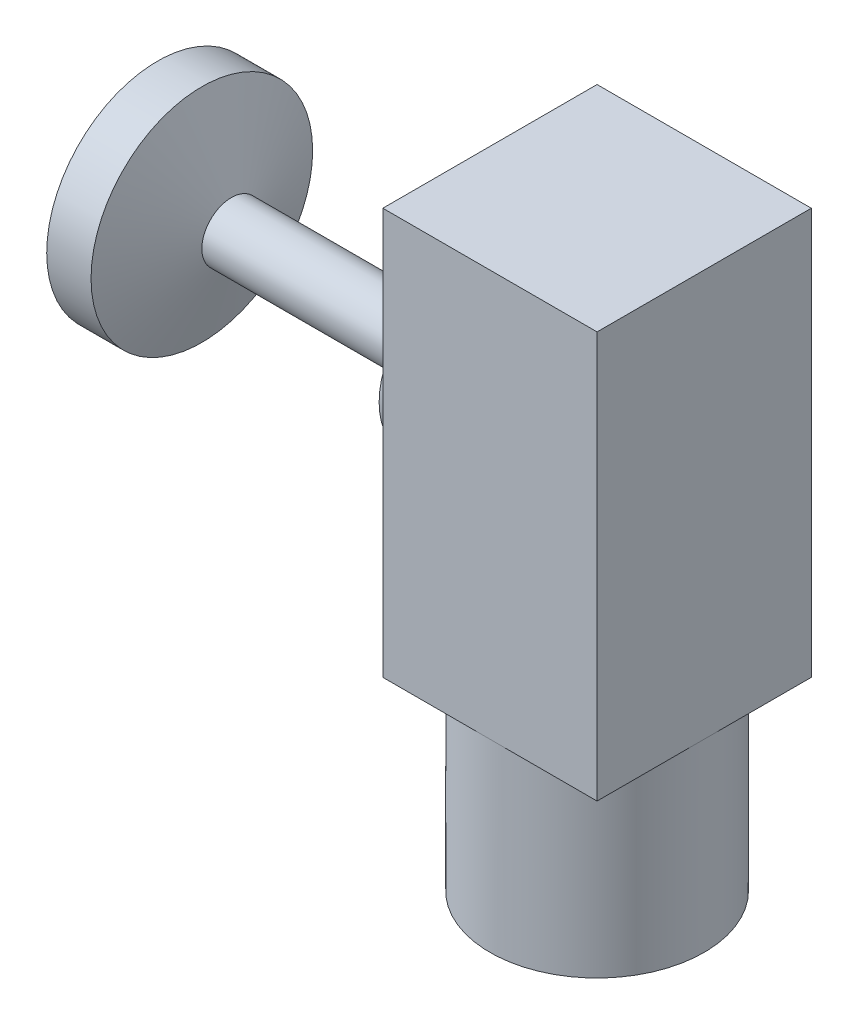
SolidWorks part; units mm, degrees
ref_plane "前视基准面" through (0, 0, 0) normal (0, 0, 1) x (1, 0, 0)
ref_plane "上视基准面" through (0, 0, 0) normal (0, 1, 0) x (1, 0, 0)
ref_plane "右视基准面" through (0, 0, 0) normal (1, 0, 0) x (0, 0, -1)
other "Configuration Table"
sketch "草图1" plane through (0, 0, 0) normal (0, 0, 1) x (1, 0, 0)
  line L0 (-10, 15) -> (-10, 0)
  line L2 (-10, 0) -> (35, 0)
  line L3 (-10, 15) -> (-4, 15)
  line L4 (-4, 15) -> (0, 4)
  line L7 (0, 4) -> (30, 4)
  line L9 (30, 4) -> (30, 10)
  line L10 (30, 10) -> (35, 10)
  line L14 (35, 0) -> (35, 10)
  point P5 (0, 0)
  dimension "D1" = 10
  dimension "D2" = 15
  dimension "D3" = 10
  dimension "D4" = 6
  dimension "D5" = 30
  dimension "D6" = 4
  dimension "D7" = 5
revolve "旋转3" add sketch "草图1" angle 360 about L2
sketch "草图2" plane through (35, 0, 0) normal (1, 0, 0) x (0, 0, -1)
  line L1 (-14.5, -27.5) -> (14.5, -27.5)
  line L2 (-14.5, -27.5) -> (-14.5, 27.5)
  line L3 (-14.5, 27.5) -> (14.5, 27.5)
  line L4 (14.5, -27.5) -> (14.5, 27.5)
  line L5 (-14.5, -27.5) -> (14.5, 27.5) construction
  line L6 (-14.5, 27.5) -> (14.5, -27.5) construction
  point P0 (0, 0)
  dimension "D1" = 29
  dimension "D2" = 55
extrude "凸台-拉伸1" add sketch "草图2" along normal blind 29
sketch "草图3" plane through (0, -27.5, 0) normal (0, -1, 0) x (1, 0, 0)
  line L0 (35, 14.5) -> (64, -14.5) construction
  line L1 (64, 14.5) -> (35, -14.5) construction
  circle A0 centre (49.5, 0) radius 14.5
  point P10 (0, 0)
  point P11 (49.5, 0)
  dimension "D1" = 29
extrude "凸台-拉伸2" add sketch "草图3" along normal blind 25
